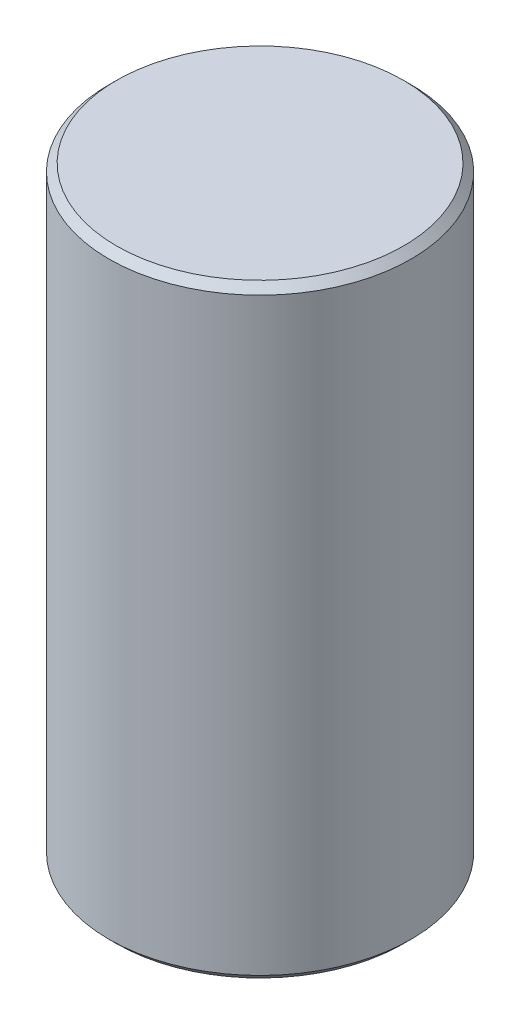
SolidWorks part; units mm, degrees
material "AISI 1045 Steel, cold drawn"
ref_plane "Front Plane" through (0, 0, 0) normal (0, 0, 1) x (1, 0, 0)
ref_plane "Top Plane" through (0, 0, 0) normal (0, 1, 0) x (1, 0, 0)
ref_plane "Right Plane" through (0, 0, 0) normal (1, 0, 0) x (0, 0, -1)
sketch "Sketch1" plane through (0, 0, 0) normal (0, 1, 0) x (1, 0, 0)
  circle A0 centre (0, 0) radius 2.5
  dimension "D1" = 5
extrude "Boss-Extrude1" add sketch "Sketch1" along normal mid plane 10
chamfer "Chamfer1" distance 0.125 angle 45 2 edges at (0, -5, 2.5) (0, 5, 2.5)
